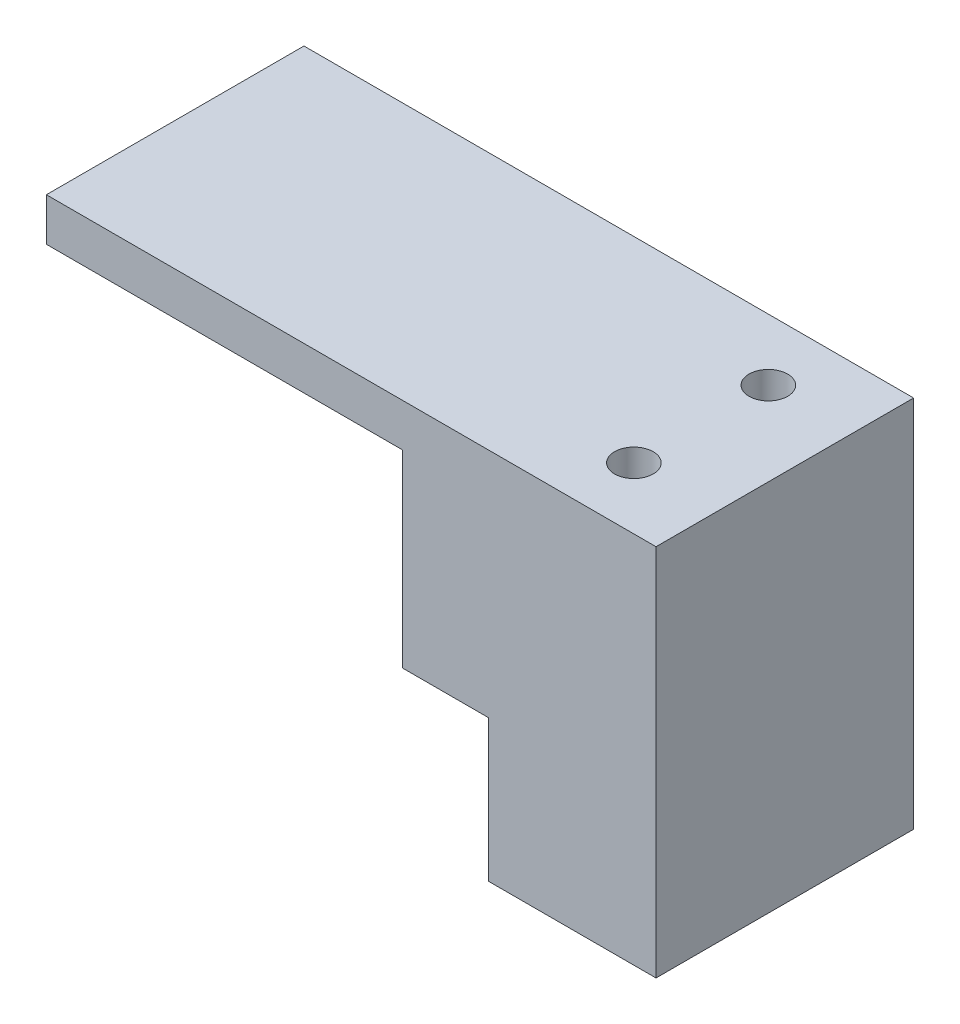
SolidWorks part; units mm, degrees
ref_plane "Front Plane" through (0, 0, 0) normal (0, 0, 1) x (1, 0, 0)
ref_plane "Top Plane" through (0, 0, 0) normal (0, 1, 0) x (1, 0, 0)
ref_plane "Right Plane" through (0, 0, 0) normal (1, 0, 0) x (0, 0, -1)
sketch "Sketch1" plane through (0, 0, 0) normal (0, 1, 0) x (1, 0, 0)
  line L0 (9.75, 0) -> (9.75, 7.1699) construction
  line L1 (0, 0) -> (19.5, 0)
  line L2 (0, 0) -> (0, 30)
  line L3 (0, 30) -> (19.5, 30)
  line L4 (19.5, 0) -> (19.5, 30)
  line L5 (9.75, 7.1699) -> (9.75, 22.8301) construction
  line L6 (9.75, 22.8301) -> (9.75, 30) construction
  circle A0 centre (9.75, 22.8301) radius 2.25
  circle A1 centre (9.75, 7.1699) radius 2.25
  dimension "D3" = 4.5
  dimension "D1" = 19.5
  dimension "D2" = 30
extrude "Boss-Extrude1" add sketch "Sketch1" along normal blind 16.5
sketch "Sketch2" plane through (0, 16.5, 0) normal (0, 1, 0) x (1, 0, 0)
  line L0 (0, 30) -> (-10, 30)
  line L1 (-10, 30) -> (-10, 0)
  line L2 (-10, 0) -> (0, 0)
  line L4 (0, 30) -> (0, 0)
  line L5 (0, 0) -> (19.5, 0)
  line L6 (19.5, 0) -> (19.5, 30)
  line L7 (19.5, 30) -> (0, 30)
  line L9 (0, 0) -> (19.5, 0)
  line L10 (19.5, 0) -> (19.5, 30)
  line L11 (19.5, 30) -> (0, 30)
  circle A0 centre (9.75, 22.8301) radius 2.25
  circle A1 centre (9.75, 7.1699) radius 2.25
  dimension "D2" = 10
  dimension "D1" = 0
extrude "Boss-Extrude2" add sketch "Sketch2" along normal blind 22
sketch "Sketch3" plane through (0, 38.5, 0) normal (0, 1, 0) x (1, 0, 0)
  line L0 (-10, 30) -> (-51.5, 30)
  line L1 (-51.5, 30) -> (-51.5, 0)
  line L2 (-51.5, 0) -> (-10, 0)
  line L4 (19.5, 30) -> (-10, 30)
  line L5 (-10, 30) -> (-10, 0)
  line L6 (-10, 0) -> (19.5, 0)
  line L7 (19.5, 0) -> (19.5, 30)
  line L8 (19.5, 30) -> (-10, 30)
  line L10 (-10, 0) -> (19.5, 0)
  line L11 (19.5, 0) -> (19.5, 30)
  circle A0 centre (9.75, 22.8301) radius 2.25
  circle A1 centre (9.75, 7.1699) radius 2.25
  dimension "D2" = 41.5
  dimension "D1" = 0
extrude "Boss-Extrude3" add sketch "Sketch3" along normal blind 5
sketch "Sketch4" plane through (0, 43.5, 0) normal (0, 1, 0) x (1, 0, 0)
  line L0 (-51.5, 0) -> (-11.5, 0) construction
  line L1 (-51.5, 0) -> (19.5, 0) construction
  line L2 (-31.5, 0) -> (-31.5, 30) construction
  line L3 (19.5, 30) -> (-51.5, 30) construction
  dimension "D1" = 40
